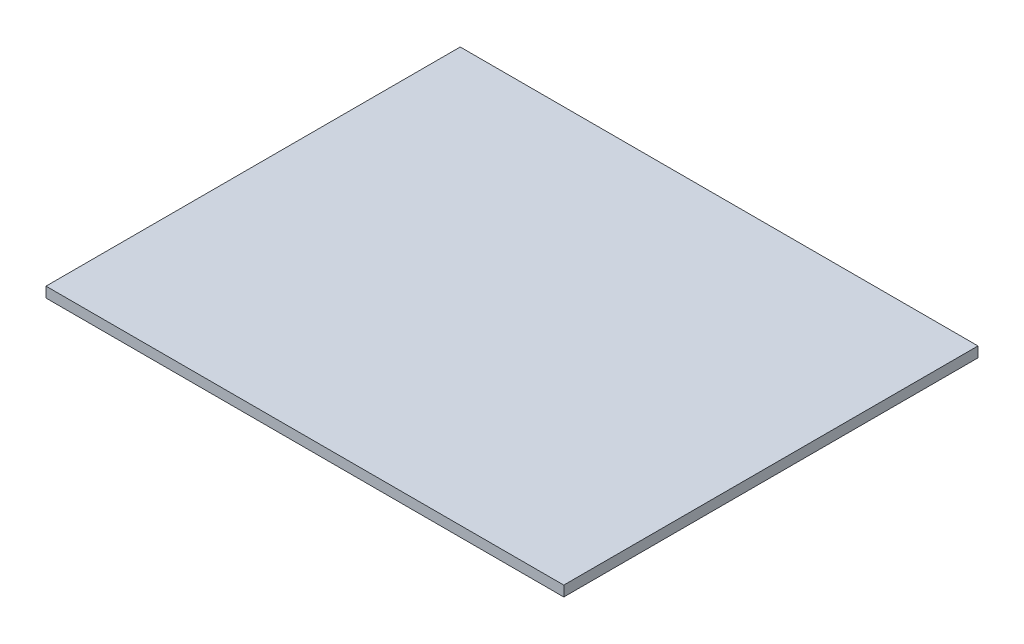
SolidWorks part; units mm, degrees
ref_plane "前视基准面" through (0, 0, 0) normal (0, 0, 1) x (1, 0, 0)
ref_plane "上视基准面" through (0, 0, 0) normal (0, 1, 0) x (1, 0, 0)
ref_plane "右视基准面" through (0, 0, 0) normal (1, 0, 0) x (0, 0, -1)
sketch "草图1" plane through (0, 0, 0) normal (0, 0, 1) x (1, 0, 0)
  line L0 (-350, -3.5) -> (150, -3.5)
  line L1 (-58.3078, -3.5) -> (-26.545, -3.5) construction
  dimension "D1" = 350
  dimension "D2" = 150
extrude "拉伸-薄壁1" add sketch "草图1" along normal mid plane 400 thin
